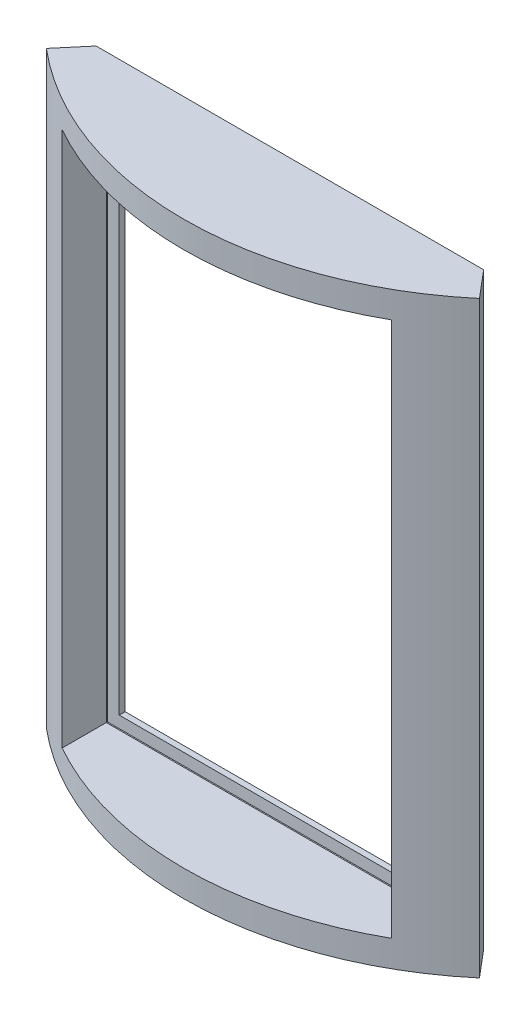
SolidWorks part; units mm, degrees
ref_plane "Front Plane" through (0, 0, 0) normal (0, 0, 1) x (1, 0, 0)
ref_plane "Top Plane" through (0, 0, 0) normal (0, 1, 0) x (1, 0, 0)
ref_plane "Right Plane" through (0, 0, 0) normal (1, 0, 0) x (0, 0, -1)
sketch "Sketch1" plane through (0, 0, 0) normal (0, 1, 0) x (1, 0, 0)
  line L0 (-36.7968, -43.5315) -> (-32.9235, -38.9493)
  line L1 (32.9235, -38.9493) -> (36.7968, -43.5315)
  line L2 (0, 0) -> (0, 80) construction
  line L3 (-32.9235, -38.9493) -> (32.9235, -38.9493)
  arc A0 (-36.7968, -43.5315) -> (36.7968, -43.5315) centre (0, 0) ccw
  arc A1 (-32.9235, -38.9493) -> (32.9235, -38.9493) centre (0, 0) ccw construction
  point P6 (0, -57)
  dimension "D1" = 57
  dimension "D2" = 51
  dimension "D3" = 80
extrude "Boss-Extrude1" add sketch "Sketch1" along normal mid plane 100
sketch "Sketch2" plane through (0, 0, 38.9493) normal (0, 0, -1) x (-1, 0, 0)
  line L1 (-28, -45.5) -> (28, -45.5)
  line L2 (-28, -45.5) -> (-28, 45.5)
  line L3 (-28, 45.5) -> (28, 45.5)
  line L4 (28, -45.5) -> (28, 45.5)
  line L5 (-28, -45.5) -> (28, 45.5) construction
  line L6 (-28, 45.5) -> (28, -45.5) construction
  point P0 (0, 0)
  dimension "D1" = 91
  dimension "D2" = 56
extrude "Cut-Extrude1" cut sketch "Sketch2" against normal through all
sketch "Sketch3" plane through (0, 0, 38.9493) normal (0, 0, -1) x (-1, 0, 0)
  line L1 (-30, -47.5) -> (30, -47.5)
  line L2 (-30, -47.5) -> (-30, 47.5)
  line L3 (-30, 47.5) -> (30, 47.5)
  line L4 (30, -47.5) -> (30, 47.5)
  line L5 (-30, -47.5) -> (30, 47.5) construction
  line L6 (-30, 47.5) -> (30, -47.5) construction
  point P0 (0, 0)
  dimension "D1" = 95
  dimension "D2" = 60
extrude "Cut-Extrude2" cut sketch "Sketch3" against normal blind 2.2 from offset 1
